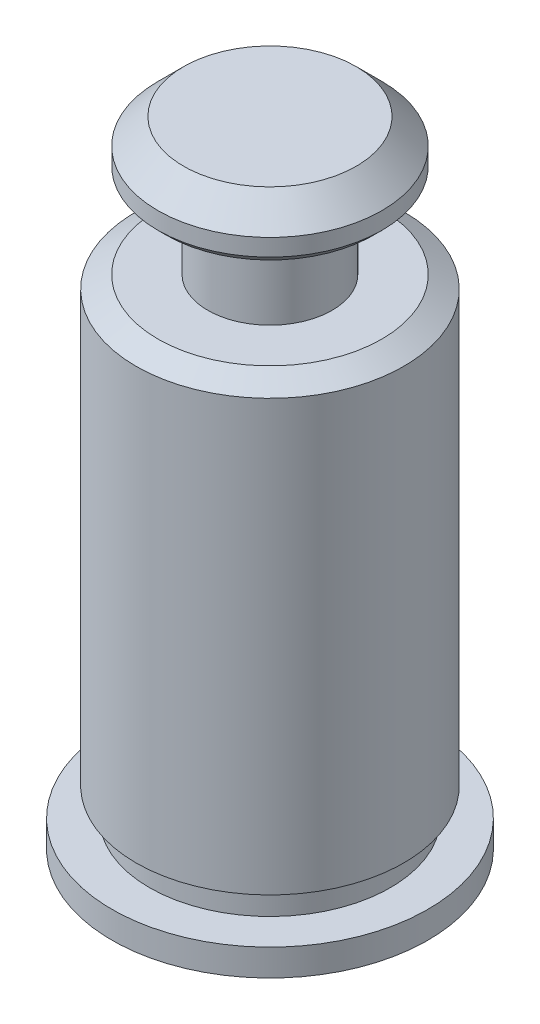
SolidWorks part; units mm, degrees
ref_plane "Plane1" through (0, 0, 0) normal (0, 0, 1) x (1, 0, 0)
ref_plane "Plane2" through (0, 0, 0) normal (0, 1, 0) x (1, 0, 0)
ref_plane "Plane3" through (0, 0, 0) normal (1, 0, 0) x (0, 0, -1)
sketch "BodySke" plane through (0, 0, 0) normal (0, 0, 1) x (1, 0, 0)
  line L0 (2.69, 0) -> (3.175, 0)
  line L1 (3.175, 0) -> (3.175, 0.538)
  line L2 (3.175, 0.538) -> (2.421, 0.538)
  line L3 (1.25, 10) -> (1.25, 11.72)
  line L4 (2.69, 1.1029) -> (2.421, 1.1029)
  line L5 (2.421, 1.1029) -> (2.421, 0.538)
  line L6 (2.69, 0.0051) -> (2.69, 0)
  line L7 (0, 0.0051) -> (2.69, 0.0051)
  line L8 (2.25, 10) -> (1.25, 10)
  line L9 (0, 0) -> (0, 15.24) construction
  line L10 (1.25, 11.72) -> (2.0783, 11.72)
  line L11 (2.69, 9.746) -> (2.69, 1.1029)
  line L12 (2.0783, 11.72) -> (2.25, 11.8917)
  line L13 (0, 0.0051) -> (0, 12.75)
  line L14 (2.25, 11.8917) -> (2.25, 12.235)
  line L15 (2.25, 12.235) -> (1.735, 12.75)
  line L16 (1.735, 12.75) -> (0, 12.75)
  line L17 (2.25, 10) -> (2.69, 9.746)
  dimension "H_dia" = 6.35
  dimension "C_dia" = 5.38
  dimension "Length" = 10
  dimension "Clinching_ht" = 0.538
  dimension "Groove_wid" = 0.5649
  dimension "Groove_dia" = 4.842
  dimension "D1" = 0.0051
  dimension "B_dia" = 4.5
  dimension "A_dia" = 2.5
  dimension "S_dim" = 1.72
  dimension "M_dim" = 2.75
  dimension "D2" = 45
  dimension "Top_chamfer_ht" = 0.515
  dimension "D3" = 45
  dimension "Under_chamfer_ht" = 0.1717
  dimension "D4" = 30
revolve "Body" add sketch "BodySke" angle 360 about L9
ref_plane "Plane4" through (0, -0.5486, 0) normal (0, 1, 0) x (-1, 0, 0)
equation "' \"Length@BodySke\" = 10"
equation "' \"A_dia@BodySke\" = 2.5"
equation "' \"B_dia@BodySke\" = 4.5"
equation "' \"C_dia@BodySke\" = 5.38"
equation "' \"S_dim@BodySke\" = 1.72"
equation "' \"M_dim@BodySke\" = 2.75"
equation "' \"H_dia@BodySke\" = 6.35"
equation "\"Top_chamfer_ht@BodySke\" = ( \"M_dim@BodySke\" - \"S_dim@BodySke\" ) * 0.5"
equation "\"Under_chamfer_ht@BodySke\" = \"Top_chamfer_ht@BodySke\" / 3"
equation "\"Clinching_ht@BodySke\" = \"C_dia@BodySke\" * 0.1"
equation "\"Groove_dia@BodySke\" = \"C_dia@BodySke\" * 0.9"
equation "\"Groove_wid@BodySke\" = \"Clinching_ht@BodySke\" * 1.05"
